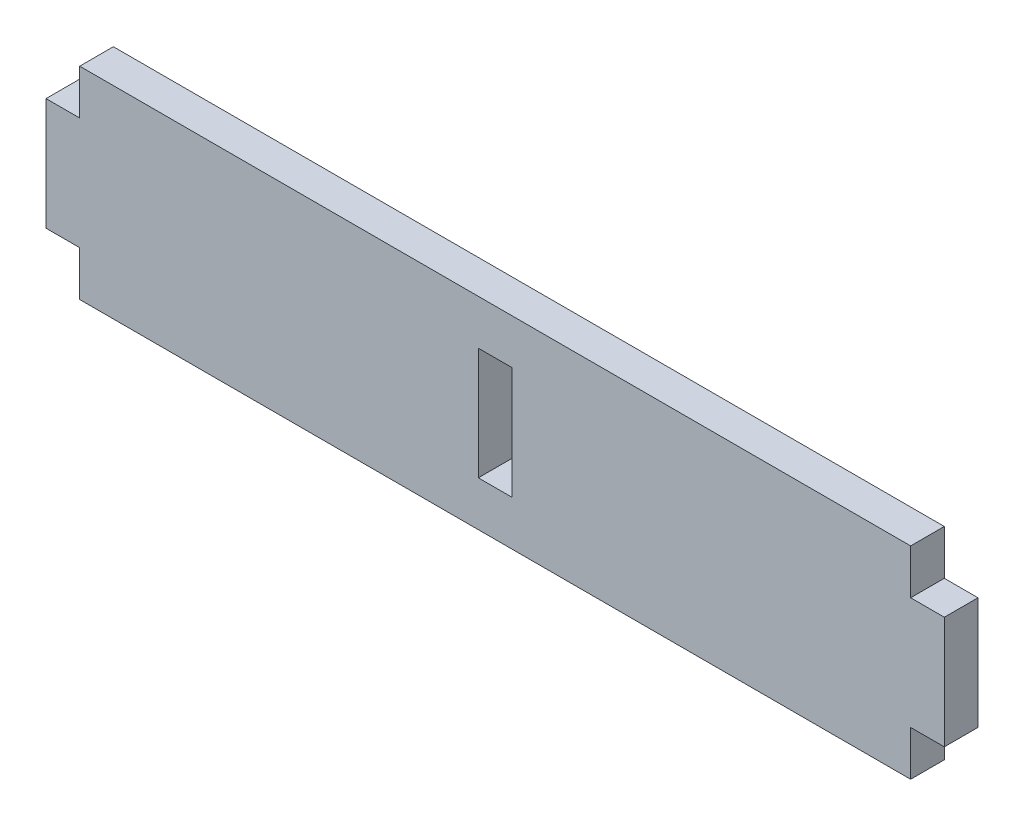
SolidWorks part; units mm, degrees
ref_plane "前基準面" through (0, 0, 0) normal (0, 0, 1) x (1, 0, 0)
ref_plane "上基準面" through (0, 0, 0) normal (0, 1, 0) x (1, 0, 0)
ref_plane "右基準面" through (0, 0, 0) normal (1, 0, 0) x (0, 0, -1)
sketch "草圖1" plane through (0, 0, 0) normal (0, 0, 1) x (1, 0, 0)
  line L0 (0, 9) -> (0, -9) construction
  line L1 (-37, 9) -> (37, 9)
  line L2 (-37, 9) -> (-37, -9)
  line L3 (-37, -9) -> (37, -9)
  line L4 (37, 9) -> (37, -9)
  line L5 (-37, 9) -> (37, -9) construction
  line L6 (-37, -9) -> (37, 9) construction
  line L7 (-37, 5) -> (-40, 5)
  line L8 (-37, 5) -> (-37, -5)
  line L9 (-37, -5) -> (-40, -5)
  line L10 (-40, 5) -> (-40, -5)
  line L11 (37, -5) -> (40, -5)
  line L12 (40, 5) -> (40, -5)
  line L13 (37, 5) -> (40, 5)
  line L14 (37, 5) -> (37, -5)
  point P0 (0, 0)
  point P10 (-40, 0)
  dimension "D1" = 18
  dimension "D2" = 74
  dimension "D3" = 3
  dimension "D4" = 10
extrude "填料-伸長1" add sketch "草圖1" along normal blind 3 contours L7 L10 L9 L2 | L4 L1 L2 L3 | L13 L4 L11 L12
sketch "草圖2" plane through (0, 0, 3) normal (0, 0, 1) x (1, 0, 0)
  line L0 (0, 9) -> (0, -9) construction
  line L1 (-37, 9) -> (37, 9) construction
  line L2 (-37, -9) -> (37, -9) construction
  line L4 (-1.5, 5) -> (1.5, 5)
  line L5 (-1.5, 5) -> (-1.5, -5)
  line L6 (-1.5, -5) -> (1.5, -5)
  line L7 (1.5, 5) -> (1.5, -5)
  line L8 (-1.5, 5) -> (1.5, -5) construction
  line L9 (-1.5, -5) -> (1.5, 5) construction
  point P6 (0, 0)
  dimension "D1" = 10
  dimension "D2" = 3
extrude "除料-伸長1" cut sketch "草圖2" against normal blind 3
